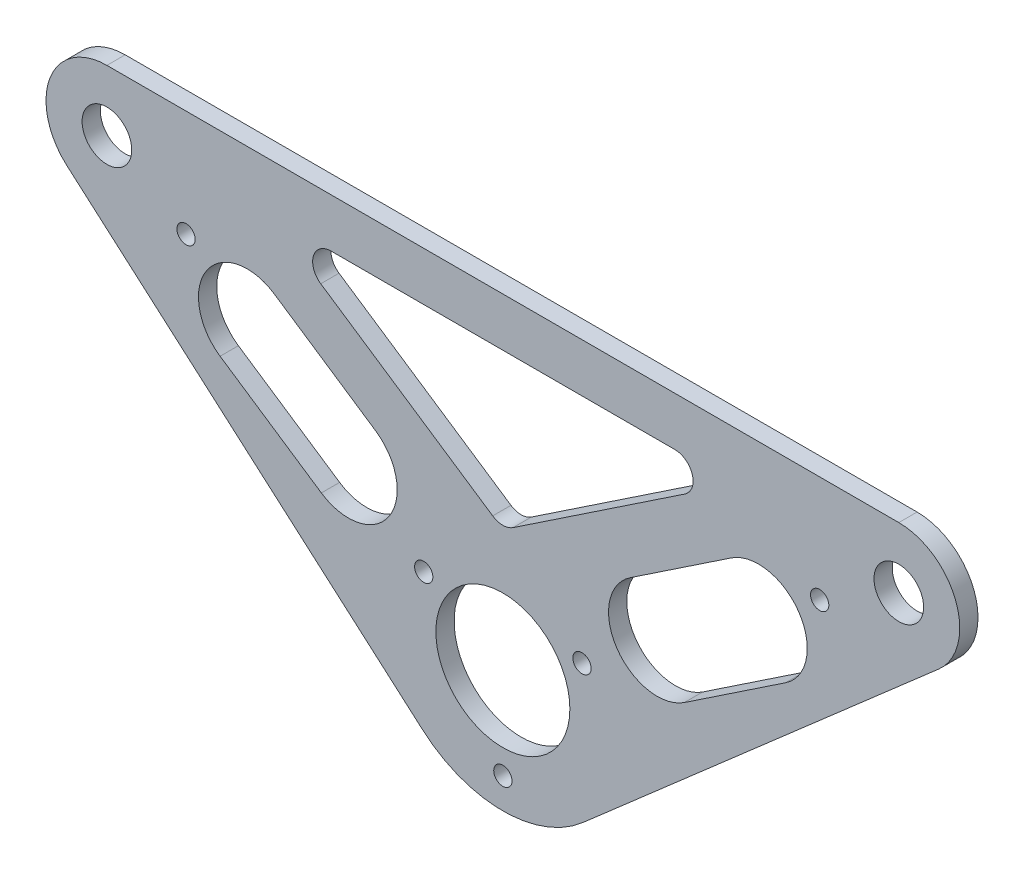
SolidWorks part; units mm, degrees
material "Acrylic (Medium-high impact)"
ref_plane "Front Plane" through (0, 0, 0) normal (0, 0, 1) x (1, 0, 0)
ref_plane "Top Plane" through (0, 0, 0) normal (0, 1, 0) x (1, 0, 0)
ref_plane "Right Plane" through (0, 0, 0) normal (1, 0, 0) x (0, 0, -1)
sketch "Sketch1" plane through (0, 0, 0) normal (0, 0, 1) x (1, 0, 0)
  line L0 (0, 0) -> (0, 53.5) construction
  line L1 (-71.5787, 35.9687) -> (-13.1573, -15.0627)
  line L3 (71.5787, 35.9687) -> (13.1573, -15.0627)
  line L7 (-65, 53.5) -> (65, 53.5)
  line L8 (-38.1034, 45.5) -> (38.1034, 45.5)
  line L9 (-38.1034, 45.5) -> (0, 20)
  line L10 (38.1034, 45.5) -> (0, 20)
  line L11 (-41.9688, 28.0868) -> (-25.3475, 16.9633) construction
  line L12 (-37.5194, 34.7353) -> (-20.8981, 23.6118)
  line L13 (-46.4182, 21.4383) -> (-29.7969, 10.3148)
  line L14 (-65, 43.5) -> (0, 0) construction
  line L15 (41.9688, 28.0868) -> (25.3475, 16.9633) construction
  line L16 (37.5194, 34.7353) -> (20.8981, 23.6118)
  line L17 (46.4182, 21.4383) -> (29.7969, 10.3148)
  arc A0 (-13.1573, -15.0627) -> (13.1573, -15.0627) centre (0, 0) ccw
  arc A1 (-65, 53.5) -> (-71.5787, 35.9687) centre (-65, 43.5) ccw
  arc A2 (-71.5787, 35.9687) -> (-65, 53.5) centre (-65, 43.5) ccw construction
  arc A3 (0, 20) -> (-13.1573, -15.0627) centre (0, 0) ccw construction
  arc A4 (71.5787, 35.9687) -> (65, 53.5) centre (65, 43.5) cw construction
  arc A5 (65, 53.5) -> (71.5787, 35.9687) centre (65, 43.5) cw
  arc A6 (13.1573, -15.0627) -> (0, 20) centre (0, 0) ccw construction
  circle A7 centre (0, 0) radius 11
  circle A8 centre (-65, 43.5) radius 4.075
  circle A9 centre (65, 43.5) radius 4.075
  arc A10 (-37.5194, 34.7353) -> (-46.4182, 21.4383) centre (-41.9688, 28.0868) ccw
  arc A11 (-29.7969, 10.3148) -> (-20.8981, 23.6118) centre (-25.3475, 16.9633) ccw
  arc A12 (37.5194, 34.7353) -> (46.4182, 21.4383) centre (41.9688, 28.0868) cw
  arc A13 (29.7969, 10.3148) -> (20.8981, 23.6118) centre (25.3475, 16.9633) cw
  point P22 (-33.6582, 22.5251)
  point P31 (33.6582, 22.5251)
  dimension "D1" = 40
  dimension "D2" = 20
  dimension "D6" = 22
  dimension "D7" = 8.15
  dimension "D8" = 8.15
  dimension "D13" = 8
  dimension "D3" = 65
  dimension "D4" = 43.5
  dimension "D5" = 20
  dimension "D11" = 20
  dimension "D12" = 40.5
  dimension "D9" = 8
extrude "Boss-Extrude1" add sketch "Sketch1" along normal mid plane 3
sketch "Sketch2" plane through (0, 0, 0) normal (0, 0, 1) x (1, 0, 0)
  circle A0 centre (0, 0) radius 15 construction
  circle A1 centre (0, -15) radius 1.5
  circle A2 centre (-12.9889, 7.5009) radius 1.5
  circle A3 centre (12.9919, 7.4991) radius 1.5
  point P12 (0.001, 0)
  dimension "D1" = 30
  dimension "D2" = 3
  dimension "D3" = 3
extrude "Cut-Extrude1" cut sketch "Sketch2" against normal through all both and the other way through all
sketch "Sketch3" plane through (0, 0, 0) normal (0, 0, 1) x (1, 0, 0)
  circle A0 centre (-65, 43.5) radius 15 construction
  circle A1 centre (-65, 58.5) radius 1.5
  circle A2 centre (-52.0096, 36) radius 1.5
  circle A3 centre (-77.9904, 36) radius 1.5
  dimension "D1" = 3
  dimension "D2" = 30
  dimension "D3" = 3
extrude "Cut-Extrude2" cut sketch "Sketch3" against normal through all both and the other way through all
mirror "Mirror1" about plane through (0, 0, 0) normal (1, 0, 0) of "Cut-Extrude2"
fillet "Fillet2" radius 3 3 edges at (-38.1034, 45.5, 0) (38.1034, 45.5, 0) (0, 20, 0)
equation "\"D8@Sketch1\"=\"D7@Sketch1\""
